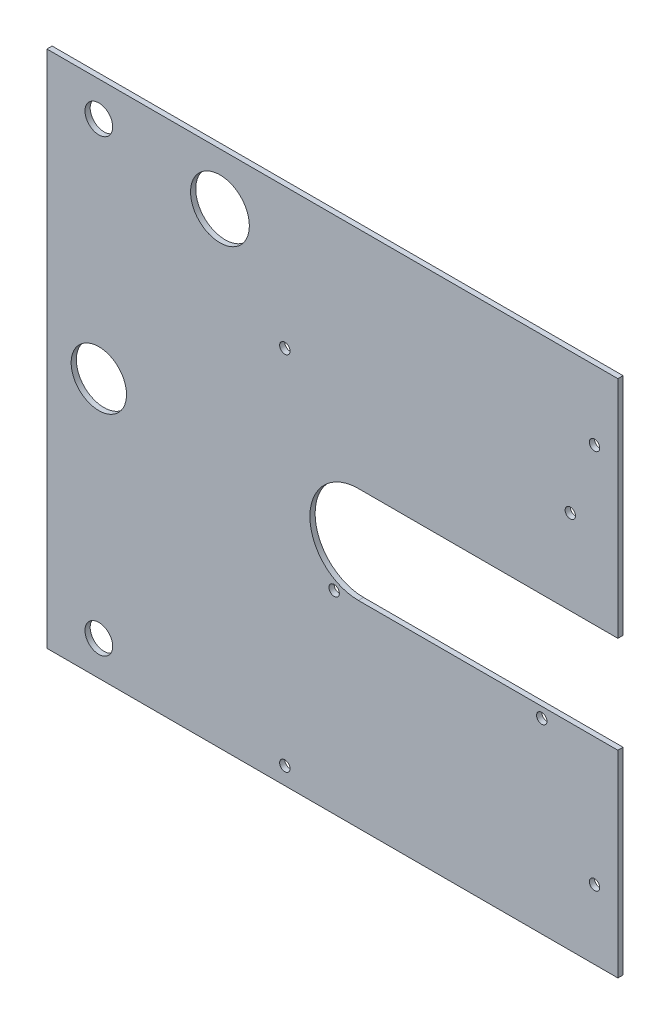
SolidWorks part; units mm, degrees
material "Alliage 1060"
ref_plane "Plan de face" through (0, 0, 0) normal (0, 0, 1) x (1, 0, 0)
ref_plane "Plan de dessus" through (0, 0, 0) normal (0, 1, 0) x (1, 0, 0)
ref_plane "Plan de droite" through (0, 0, 0) normal (1, 0, 0) x (0, 0, -1)
sketch "Esquisse1" plane through (0, 0, 0) normal (0, 0, 1) x (1, 0, 0)
  line L1 (0, 75) -> (165, 75)
  line L2 (0, 75) -> (0, -75)
  line L3 (0, -75) -> (165, -75)
  line L4 (165, 75) -> (165, -75)
  dimension "D1" = 165
  dimension "D2" = 150
extrude "Boss.-Extru.1" add sketch "Esquisse1" along normal blind 1.5
sketch "Esquisse2" plane through (0, 0, 1.5) normal (0, 0, 1) x (1, 0, 0)
  line L0 (90, 10) -> (165, 10)
  line L2 (165, -18) -> (90, -18)
  line L3 (90, -18) -> (165, -18) construction
  line L4 (165, -75) -> (165, 75) construction
  line L5 (0, -75) -> (165, -75) construction
  circle A0 centre (158.25, 55) radius 1.5
  circle A1 centre (158.25, -55) radius 1.5
  circle A2 centre (151.25, 34.5) radius 1.5
  circle A3 centre (83, -19) radius 1.5
  circle A4 centre (143, -21) radius 1.5
  arc A5 (165, 10) -> (165, -18) centre (165, -4) cw
  arc A6 (90, -18) -> (90, 10) centre (90, -4) cw
  circle A7 centre (15, 0) radius 8
  circle A8 centre (15, 65) radius 4
  circle A9 centre (15, -65) radius 4
  circle A10 centre (15, 65) radius 4 construction
  circle A11 centre (83, -19) radius 1.2 construction
  arc A12 (90, 10) -> (90, -18) centre (90, -4) ccw construction
  circle A14 centre (158.25, 55) radius 1.2 construction
  circle A15 centre (151.25, 34.5) radius 1.2 construction
  circle A16 centre (158.25, -55) radius 1.2 construction
  circle A17 centre (143, -21) radius 1.2 construction
  circle A18 centre (15, 0) radius 8 construction
  circle A19 centre (15, -65) radius 4 construction
  circle A20 centre (50, 60) radius 8.5
  circle A21 centre (68.75, 34.5) radius 1.5
  circle A22 centre (68.75, 34.5) radius 1.2 construction
  circle A23 centre (68.75, -70) radius 1.5
  dimension "D1" = 3
  dimension "D2" = 17
  dimension "D3" = 135
  dimension "D4" = 115
  dimension "D5" = 5
extrude "Enlèv. mat.-Extru.1" cut sketch "Esquisse2" against normal through all
